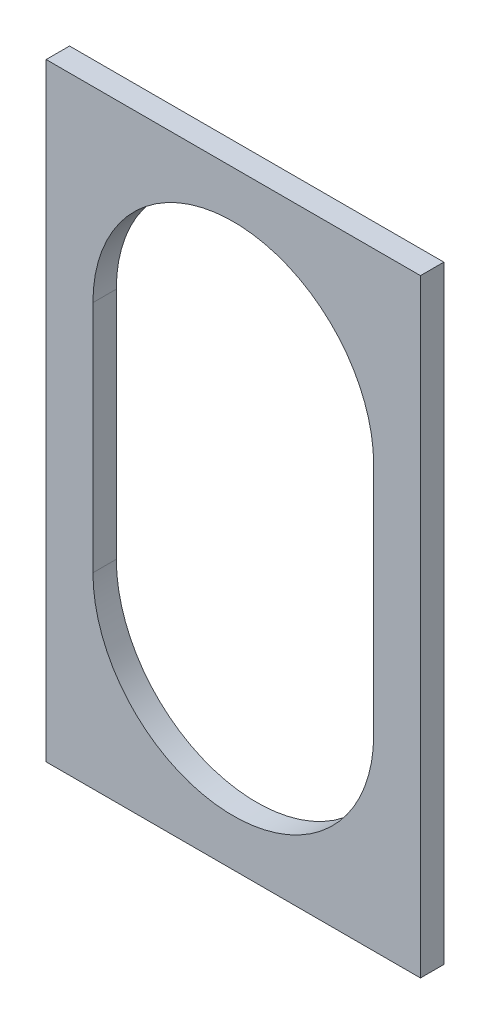
SolidWorks part; units mm, degrees
material "6061 Сплав"
ref_plane "Спереди" through (0, 0, 0) normal (0, 0, 1) x (1, 0, 0)
ref_plane "Сверху" through (0, 0, 0) normal (0, 1, 0) x (1, 0, 0)
ref_plane "Справа" through (0, 0, 0) normal (1, 0, 0) x (0, 0, -1)
other "Configuration Table"
sketch "Эскиз1" plane through (0, 0, 0) normal (0, 0, 1) x (1, 0, 0)
  line L0 (0, 25) -> (0, -25) construction
  line L2 (30, 25) -> (30, -25)
  line L3 (-30, 25) -> (-30, -25)
  line L4 (40, -65) -> (-40, -65)
  line L5 (40, -65) -> (40, 65)
  line L6 (40, 65) -> (-40, 65)
  line L7 (-40, -65) -> (-40, 65)
  line L8 (40, -65) -> (-40, 65) construction
  line L9 (40, 65) -> (-40, -65) construction
  arc A0 (30, 25) -> (-30, 25) centre (0, 25) ccw
  arc A1 (-30, -25) -> (30, -25) centre (0, -25) ccw
  point P3 (0, 55)
  point P4 (0, 0)
  point P5 (0, 0)
  dimension "D1" = 60
  dimension "D2" = 110
  dimension "D3" = 10
  dimension "D4" = 10
extrude "Бобышка-Вытянуть1" add sketch "Эскиз1" along normal blind 5
